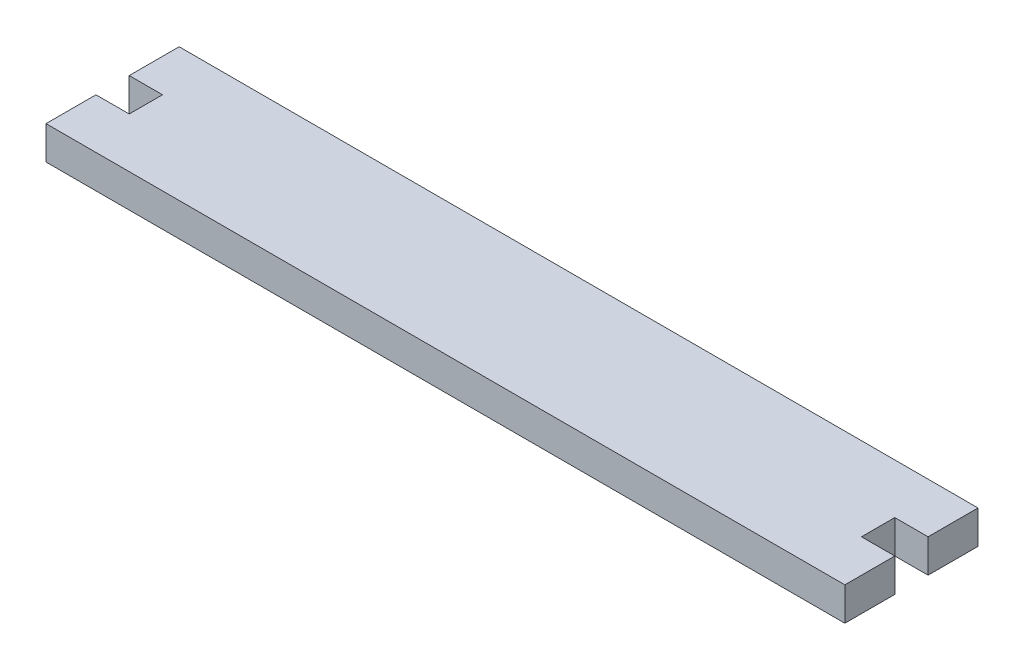
SolidWorks part; units mm, degrees
ref_plane "Front Plane" through (0, 0, 0) normal (0, 0, 1) x (1, 0, 0)
ref_plane "Top Plane" through (0, 0, 0) normal (0, 1, 0) x (1, 0, 0)
ref_plane "Right Plane" through (0, 0, 0) normal (1, 0, 0) x (0, 0, -1)
sketch "Sketch1" plane through (0, 0, 0) normal (0, 1, 0) x (1, 0, 0)
  line L0 (-38.1, 6.35) -> (-38.1, 1.5875)
  line L1 (38.1, -6.35) -> (-38.1, -6.35)
  line L2 (38.1, -6.35) -> (38.1, 6.35) construction
  line L3 (38.1, 6.35) -> (-38.1, 6.35)
  line L4 (-38.1, -6.35) -> (-38.1, 6.35) construction
  line L5 (38.1, -6.35) -> (-38.1, 6.35) construction
  line L6 (38.1, 6.35) -> (-38.1, -6.35) construction
  line L7 (-38.1, 1.5875) -> (-34.925, 1.5875)
  line L8 (-34.925, 1.5875) -> (-34.925, -1.5875)
  line L9 (-34.925, -1.5875) -> (-38.1, -1.5875)
  line L10 (-38.1, -1.5875) -> (-38.1, -6.35)
  line L11 (38.1, 6.35) -> (38.1, 1.5875)
  line L12 (38.1, 1.5875) -> (34.925, 1.5875)
  line L13 (34.925, 1.5875) -> (34.925, -1.5875)
  line L14 (34.925, -1.5875) -> (38.1, -1.5875)
  line L15 (38.1, -1.5875) -> (38.1, -6.35)
  point P0 (0, 0)
  point P6 (0, 0)
  point P15 (34.925, 0)
  dimension "D1" = 76.2
  dimension "D2" = 12.7
  dimension "D3" = 3.175
  dimension "D4" = 3.175
  dimension "D5" = 3.175
extrude "Boss-Extrude1" add sketch "Sketch1" along normal blind 3.175 contours L15 L1 L10 L9 L8 L7 L0 L3 L11 L12 L13 L14
